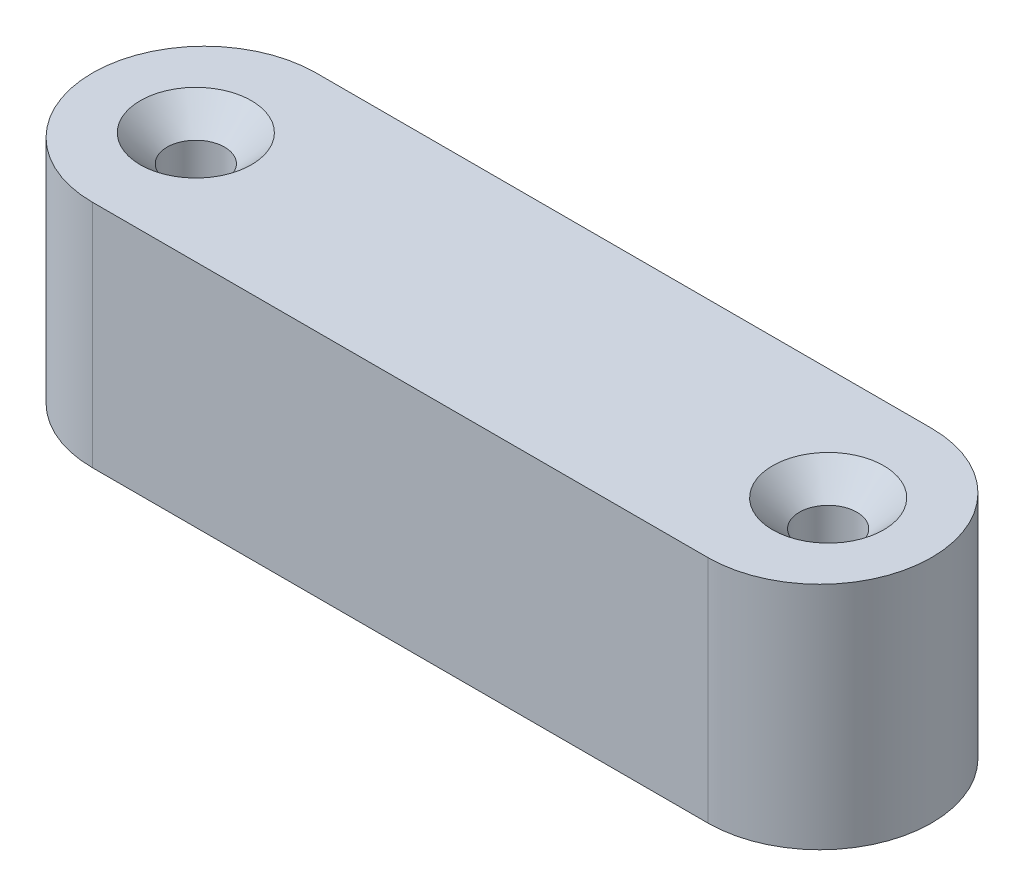
SolidWorks part; units mm, degrees
material "ABS PC"
ref_plane "Front" through (0, 0, 0) normal (0, 0, 1) x (1, 0, 0)
ref_plane "Top" through (0, 0, 0) normal (0, 1, 0) x (1, 0, 0)
ref_plane "Right" through (0, 0, 0) normal (1, 0, 0) x (0, 0, -1)
sketch "Sketch1" plane through (0, 0, 0) normal (0, 1, 0) x (1, 0, 0)
  line L0 (-20.3962, 0) -> (20.3962, 0) construction
  line L1 (-20.3962, 7.4168) -> (20.3962, 7.4168)
  line L2 (-20.3962, -7.4168) -> (20.3962, -7.4168)
  line L3 (-20.955, 0) -> (-20.955, -1.905) construction
  line L4 (-20.955, -1.905) -> (20.955, -1.905) construction
  line L5 (20.955, -1.905) -> (20.955, 0) construction
  line L6 (0, 0) -> (0, -1.905) construction
  arc A0 (-20.3962, 7.4168) -> (-20.3962, -7.4168) centre (-20.3962, 0) ccw
  arc A1 (20.3962, -7.4168) -> (20.3962, 7.4168) centre (20.3962, 0) ccw
  circle A2 centre (-20.955, 0) radius 1.905
  circle A3 centre (20.955, 0) radius 1.905
  point P3 (0, 0)
  dimension "D1" = 55.626
  dimension "D3" = 3.81
  dimension "D4" = 41.91
  dimension "D2" = 14.8336
extrude "Boss-Extrude1" add sketch "Sketch1" along normal blind 15.24
chamfer "Chamfer1" distance 1.778 angle 45 2 edges at (20.955, 15.24, 1.905) (-20.955, 15.24, 1.905)
